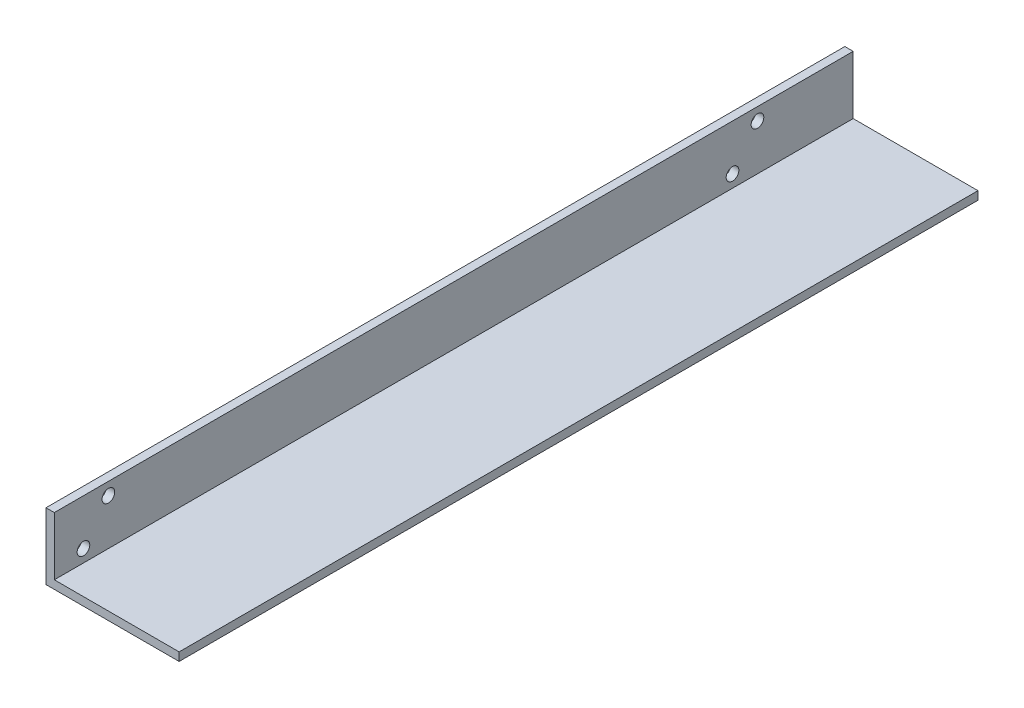
SolidWorks part; units mm, degrees
ref_plane "Front Plane" through (0, 0, 0) normal (0, 0, 1) x (1, 0, 0)
ref_plane "Top Plane" through (0, 0, 0) normal (0, 1, 0) x (1, 0, 0)
ref_plane "Right Plane" through (0, 0, 0) normal (1, 0, 0) x (0, 0, -1)
sketch "Sketch1" plane through (0, 0, 0) normal (0, 0, 1) x (1, 0, 0)
  line L0 (3.175, 3.175) -> (3.175, 25.4)
  line L1 (0, 0) -> (50.8, 0)
  line L2 (0, 0) -> (0, 25.4)
  line L5 (3.175, 3.175) -> (50.8, 3.175)
  line L6 (0, 25.4) -> (3.175, 25.4)
  line L7 (50.8, 0) -> (50.8, 3.175)
  dimension "D1" = 25.4
  dimension "D2" = 50.8
  dimension "D3" = 3.175
extrude "Boss-Extrude1" add sketch "Sketch1" along normal blind 304.8
sketch "Sketch2" plane through (0, 0, 0) normal (-1, 0, 0) x (0, 0, 1)
  circle A0 centre (36.5125, 20.6375) radius 2.413 construction
  circle A1 centre (36.5125, 20.6375) radius 2.413
  circle A2 centre (46.0375, 7.9375) radius 2.413 construction
  circle A3 centre (46.0375, 7.9375) radius 2.413
  circle A4 centre (284.1625, 20.6375) radius 2.413 construction
  circle A5 centre (284.1625, 20.6375) radius 2.413
  circle A6 centre (293.6875, 7.9375) radius 2.413 construction
  circle A7 centre (293.6875, 7.9375) radius 2.413
extrude "Cut-Extrude1" cut sketch "Sketch2" against normal up to next
